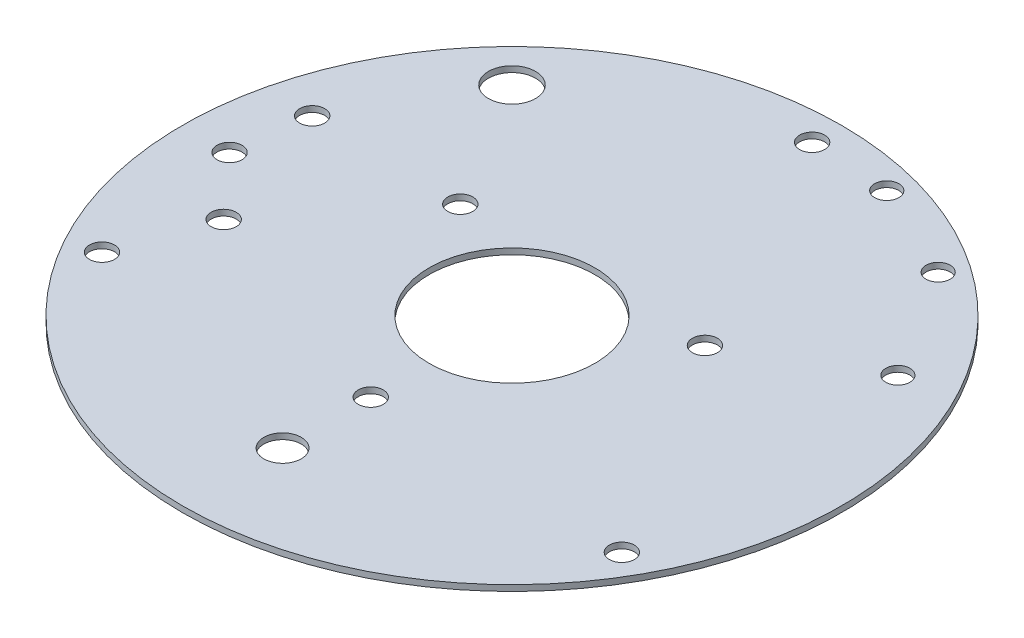
SolidWorks part; units mm, degrees
material "2.1020 (CuSn6)"
ref_plane "Front Plane" through (0, 0, 0) normal (0, 0, 1) x (1, 0, 0)
ref_plane "Top Plane" through (0, 0, 0) normal (0, 1, 0) x (1, 0, 0)
ref_plane "Right Plane" through (0, 0, 0) normal (1, 0, 0) x (0, 0, -1)
sketch "Sketch1" plane through (0, 0, 0) normal (0, 1, 0) x (1, 0, 0)
  circle A0 centre (0, 0) radius 88.9
  circle A1 centre (0, 0) radius 22.352
  circle A2 centre (-53.8734, 53.8734) radius 6.35
  circle A3 centre (0, -61.8998) radius 5.0419
  circle A5 centre (-61.341, -16.4338) radius 3.3782
  circle A6 centre (-76.2, 0) radius 3.3782
  circle A7 centre (-73.6092, 19.7104) radius 3.3782
  circle A8 centre (65.9892, 38.1) radius 3.2639
  circle A10 centre (47.3456, 67.6148) radius 3.2639
  circle A11 centre (21.3614, 79.7306) radius 3.2639
  circle A12 centre (0, 80.9625) radius 3.3782
  circle A13 centre (70.1156, -40.4813) radius 3.3782
  circle A14 centre (-70.1156, -40.4812) radius 3.3782
  circle A15 centre (0, -38.1) radius 3.3782
  circle A16 centre (-32.9956, 19.05) radius 3.3782
  circle A17 centre (32.9956, 19.05) radius 3.3782
  point P32 (0, 0)
  point P39 (0, 0)
  dimension "D1" = 3
  dimension "D2" = 3
extrude "Boss-Extrude1" add sketch "Sketch1" along normal blind 1.6002
